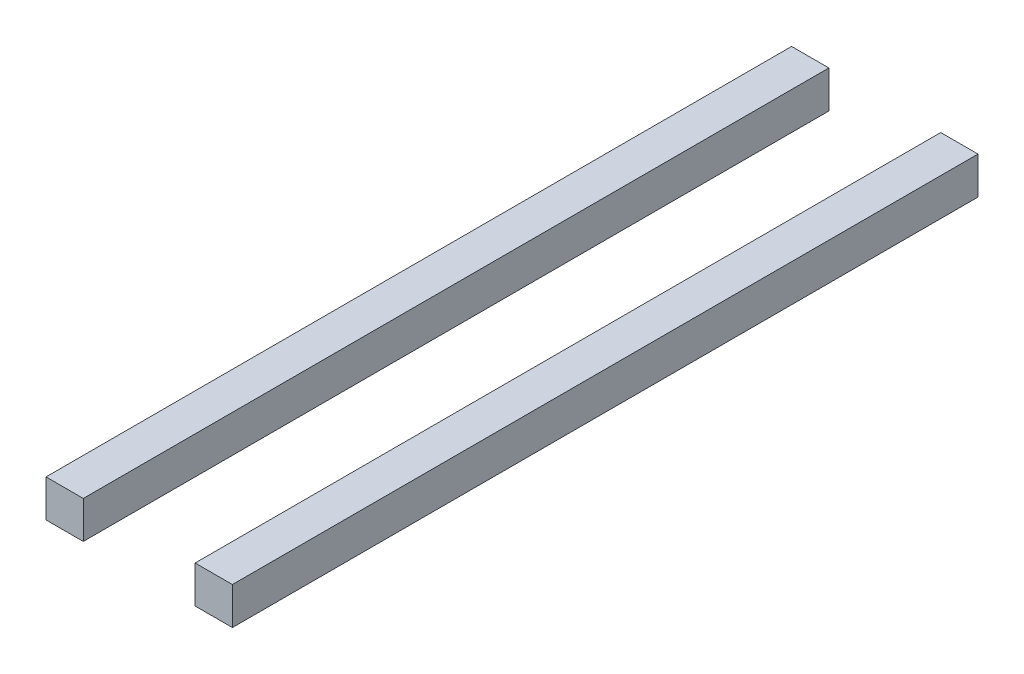
SolidWorks part; units mm, degrees
ref_plane "前视基准面" through (0, 0, 0) normal (0, 0, 1) x (1, 0, 0)
ref_plane "上视基准面" through (0, 0, 0) normal (0, 1, 0) x (1, 0, 0)
ref_plane "右视基准面" through (0, 0, 0) normal (1, 0, 0) x (0, 0, -1)
other "Configuration Table"
sketch "草图1" plane through (0, 0, 0) normal (0, 0, 1) x (1, 0, 0)
  line L1 (30, -20) -> (50, -20)
  line L2 (30, -20) -> (30, 0)
  line L3 (30, 0) -> (50, 0)
  line L4 (50, -20) -> (50, 0)
  line L5 (-50, -20) -> (-30, -20)
  line L6 (-50, -20) -> (-50, 0)
  line L7 (-50, 0) -> (-30, 0)
  line L8 (-30, -20) -> (-30, 0)
extrude "凸台-拉伸1" add sketch "草图1" against normal blind 400
